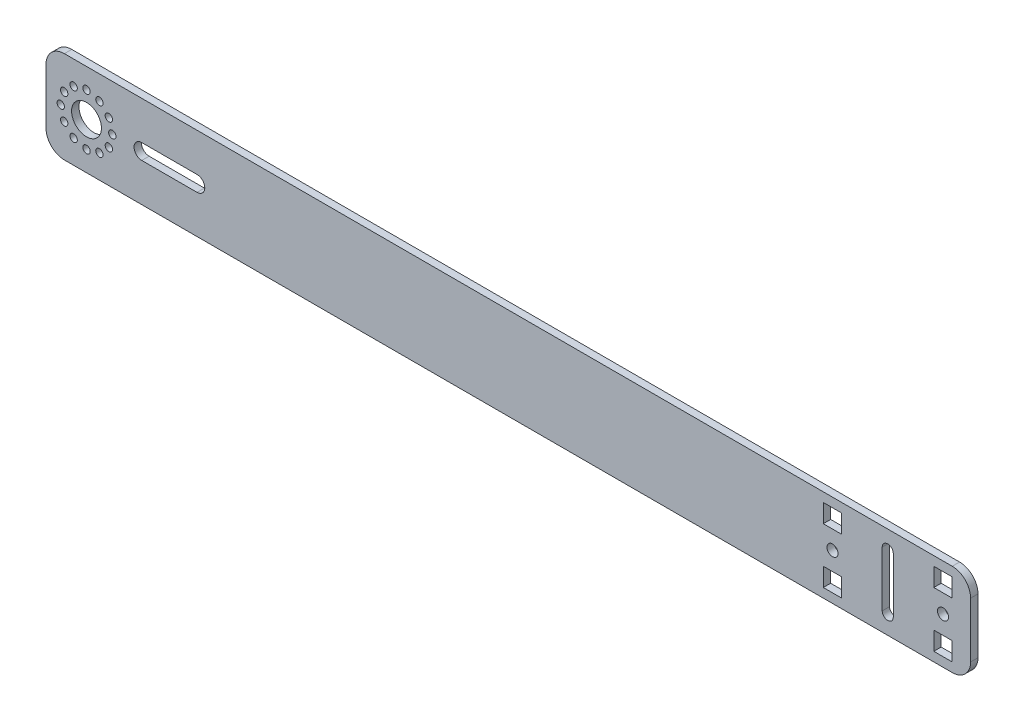
SolidWorks part; units mm, degrees
ref_plane "Plan de face" through (0, 0, 0) normal (0, 0, 1) x (1, 0, 0)
ref_plane "Plan de dessus" through (0, 0, 0) normal (0, 1, 0) x (1, 0, 0)
ref_plane "Plan de droite" through (0, 0, 0) normal (1, 0, 0) x (0, 0, -1)
sketch "Esquisse2" plane through (0, 0, 0) normal (0, 0, -1) x (-1, 0, 0)
  line L0 (-251, -12.5) -> (0, -12.5)
  line L1 (-6.2, -12.5) -> (-6.2, 12.5) construction
  line L2 (0, -12.5) -> (0, 12.5)
  line L3 (0, 12.5) -> (-251, 12.5)
  line L4 (-251, 12.5) -> (-251, -12.5)
  line L5 (-95.5557, 0) -> (0, 0) construction
  line L6 (-241, 12.5) -> (-241, -12.5) construction
  line L7 (-26, 0) -> (-41, 0) construction
  line L8 (-26, -2.1) -> (-41, -2.1)
  line L9 (-26, 2.1) -> (-41, 2.1)
  arc A0 (-26, -2.1) -> (-26, 2.1) centre (-26, 0) ccw
  arc A1 (-41, 2.1) -> (-41, -2.1) centre (-41, 0) ccw
  point P12 (-33.5, 0)
  circle B0 centre (-11, 0) radius 4.05
  circle B1 centre (-4, 0) radius 1
  circle B2 centre (-4.9378, -3.5) radius 1
  circle B3 centre (-7.5, -6.0622) radius 1
  circle B4 centre (-11, -7) radius 1
  circle B5 centre (-14.5, -6.0622) radius 1
  circle B6 centre (-17.0622, -3.5) radius 1
  circle B7 centre (-18, 0) radius 1
  circle B8 centre (-17.0622, 3.5) radius 1
  circle B9 centre (-14.5, 6.0622) radius 1
  circle B10 centre (-11, 7) radius 1
  circle B11 centre (-7.5, 6.0622) radius 1
  circle B12 centre (-4.9378, 3.5) radius 1
  line B13 (-246, -5) -> (-246, -10)
  line B14 (-246, -5) -> (-241, -5)
  line B15 (-241, -5) -> (-241, -10)
  line B16 (-246, -10) -> (-241, -10)
  line B17 (-246, 5) -> (-246, 10)
  line B18 (-246, 5) -> (-241, 5)
  line B19 (-241, 5) -> (-241, 10)
  line B20 (-246, 10) -> (-241, 10)
  line B21 (-243.5, 0) -> (-250.4724, 0) construction
  circle B22 centre (-243.5, 0) radius 1.5
  dimension "D8" = 2.1
  dimension "D1" = 25
  dimension "D2" = 11
  dimension "D3" = 230
  dimension "D4" = 15
  dimension "D5" = 5
  dimension "D7" = 15
sketch_block_instance "Block1-1"
sketch_block "Block1" parameters "D2"=2, "D3"=8.1, "D1"=7
sketch_block_instance "Trou M3 plots 5mm-1"
sketch_block "Trou M3 plots 5mm" parameters "D2"=3, "D1"=5, "D3"=5, "D4"=10
extrude "Boss.-Extru.1" add sketch "Esquisse2" against normal blind 2
fillet "Congé1" radius 5 4 edges at (0, -12.5, 1) (0, 12.5, 1) (251, 12.5, 1) (251, -12.5, 1)
sketch "Esquisse3" plane through (0, 0, 0) normal (0, 0, -1) x (-1, 0, 0)
  line L0 (-246, -10) -> (-241, -10) construction
  line L1 (-243.5, 0) -> (-242, 0) construction
  line L4 (-246, -5) -> (-246, -10) construction
  line L5 (-241, -10) -> (-241, -5) construction
  line L6 (-241, -5) -> (-246, -5) construction
  line L7 (-241, 5) -> (-241, 10) construction
  line L8 (-246, 5) -> (-241, 5) construction
  line L9 (-241, 10) -> (-246, 10) construction
  line L10 (-246, 10) -> (-246, 5) construction
  line L11 (-246, -10) -> (-241, -10)
  line L12 (-246, -5) -> (-246, -10)
  line L13 (-241, -10) -> (-241, -5)
  line L14 (-241, -5) -> (-246, -5)
  line L15 (-241, 5) -> (-241, 10)
  line L16 (-246, 5) -> (-241, 5)
  line L17 (-241, 10) -> (-246, 10)
  line L18 (-246, 10) -> (-246, 5)
  line L19 (-216, -10) -> (-211, -10)
  line L20 (-216, -5) -> (-216, -10)
  line L21 (-211, -10) -> (-211, -5)
  line L22 (-211, -5) -> (-216, -5)
  line L23 (-211, 5) -> (-211, 10)
  line L24 (-216, 5) -> (-211, 5)
  line L25 (-211, 10) -> (-216, 10)
  line L26 (-216, 10) -> (-216, 5)
  line L27 (-243.5, 0) -> (-213.5, 0) construction
  line L28 (-215, 0) -> (-213.5, 0) construction
  line L29 (-228.5, 0) -> (-228.5, -12.5) construction
  line L30 (-246, -12.5) -> (-5, -12.5) construction
  line L31 (-228.5, 0) -> (-228.5, 12.5) construction
  line L33 (-5, 12.5) -> (-246, 12.5) construction
  line L34 (-228.5, -7.5) -> (-228.5, 7.5) construction
  line L35 (-230, -7.5) -> (-230, 7.5)
  line L36 (-227, -7.5) -> (-227, 7.5)
  circle A0 centre (-243.5, 0) radius 1.5 construction
  circle A1 centre (-243.5, 0) radius 1.5
  circle A2 centre (-213.5, 0) radius 1.5
  arc A3 (-230, -7.5) -> (-227, -7.5) centre (-228.5, -7.5) ccw
  arc A4 (-227, 7.5) -> (-230, 7.5) centre (-228.5, 7.5) ccw
  point P10 (-228.5, 0)
  dimension "D2" = 3
  dimension "D3" = 5
  dimension "D4" = 5
  dimension "D1" = 2
extrude "Enlèv. mat.-Extru.1" cut sketch "Esquisse3" against normal blind 10
